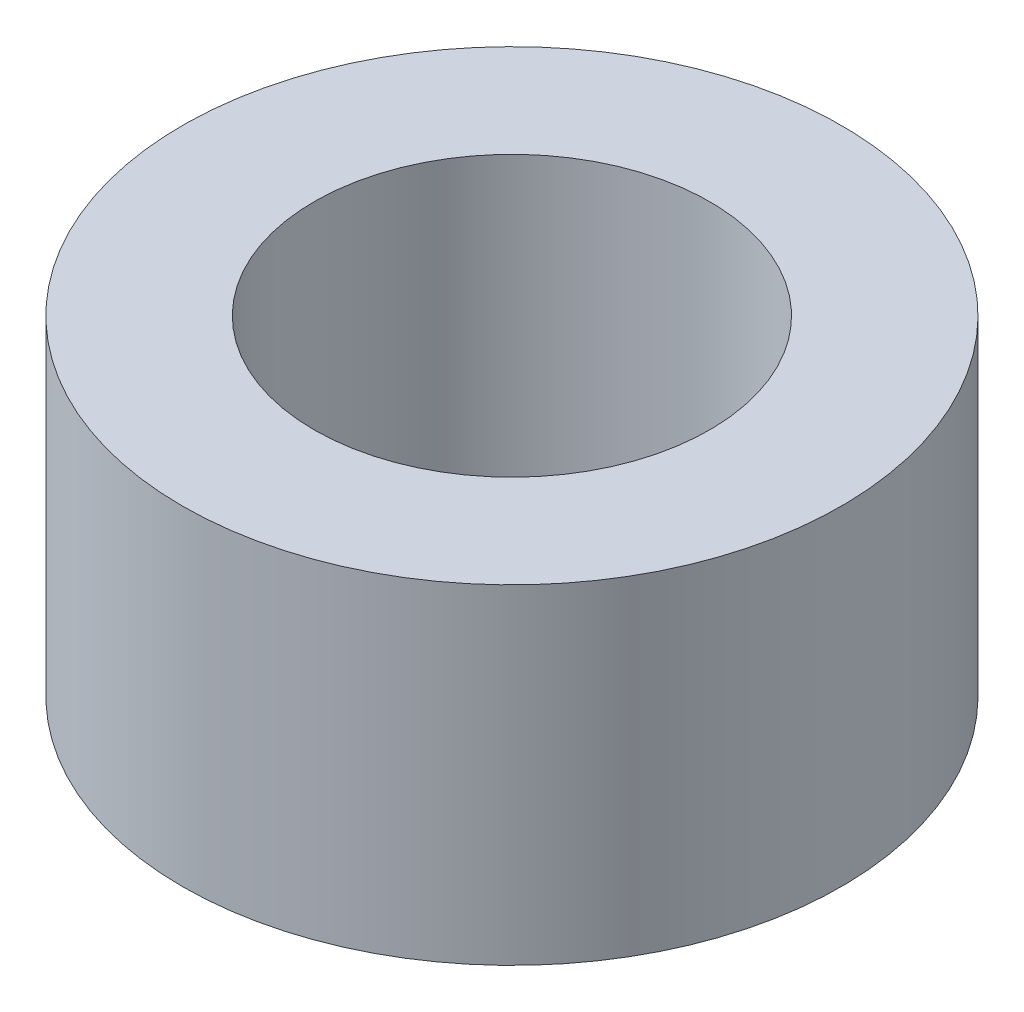
SolidWorks part; units mm, degrees
ref_plane "Front Plane" through (0, 0, 0) normal (0, 0, 1) x (1, 0, 0)
ref_plane "Top Plane" through (0, 0, 0) normal (0, 1, 0) x (1, 0, 0)
ref_plane "Right Plane" through (0, 0, 0) normal (1, 0, 0) x (0, 0, -1)
sketch "Sketch1" plane through (0, 0, 0) normal (0, 1, 0) x (1, 0, 0)
  circle A0 centre (0, 0) radius 3
  circle A1 centre (0, 0) radius 5
  dimension "D1" = 6
  dimension "D2" = 10
extrude "Boss-Extrude1" add sketch "Sketch1" along normal blind 5
